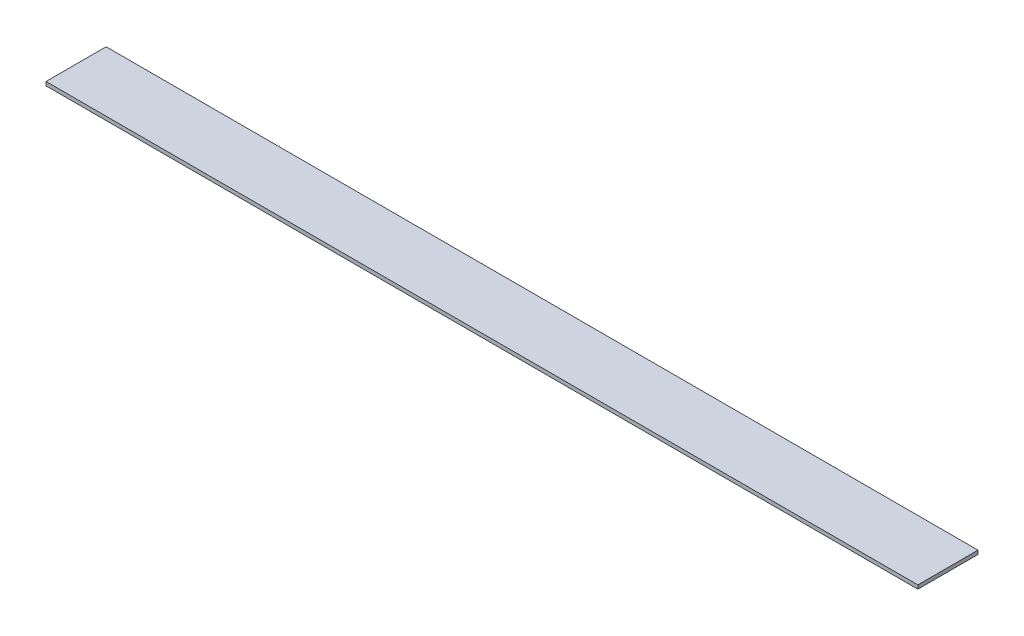
SolidWorks part; units mm, degrees
material "NEOPRENE"
ref_plane "Front" through (0, 0, 0) normal (0, 0, 1) x (1, 0, 0)
ref_plane "Top" through (0, 0, 0) normal (0, 1, 0) x (1, 0, 0)
ref_plane "Right" through (0, 0, 0) normal (1, 0, 0) x (0, 0, -1)
sketch "Sketch1" plane through (0, 0, 0) normal (0, 1, 0) x (1, 0, 0)
  line L6 (0, 0) -> (368.3, 0)
  line L7 (0, 0) -> (0, 25.4)
  line L8 (0, 25.4) -> (368.3, 25.4)
  line L9 (368.3, 0) -> (368.3, 25.4)
  dimension "D1" = 25.4
  dimension "D2" = 368.3
extrude "Boss-Extrude1" add sketch "Sketch1" along normal blind 1.5875
